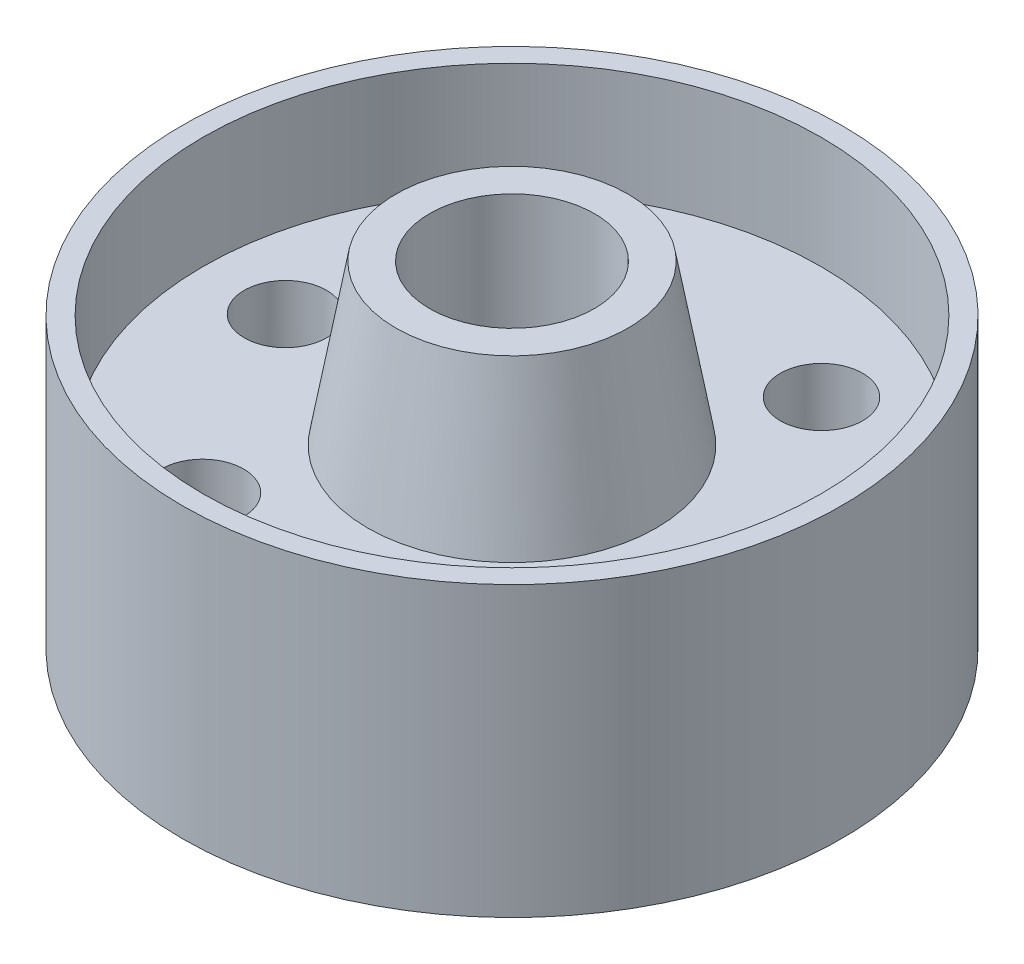
SolidWorks part; units mm, degrees
material "Plain Carbon Steel"
ref_plane "Front" through (0, 0, 0) normal (0, 0, 1) x (1, 0, 0)
ref_plane "Top" through (0, 0, 0) normal (0, 1, 0) x (1, 0, 0)
ref_plane "Right" through (0, 0, 0) normal (1, 0, 0) x (0, 0, -1)
sketch "Sketch1" plane through (0, 0, 0) normal (1, 0, 0) x (0, 0, -1)
  line L0 (0, 0) -> (-38.1, 0) construction
  line L1 (-38.1, 0) -> (-38.1, 22.098)
  line L2 (-38.1, 22.098) -> (-34.925, 22.098)
  line L3 (-34.925, 22.098) -> (-34.925, 4.826)
  line L4 (-34.925, 4.826) -> (-9.525, 4.826)
  line L5 (-9.525, 4.826) -> (-5.1986, 29.3624)
  line L6 (-5.1986, 29.3624) -> (0, 29.3624)
  line L7 (0, 29.3624) -> (0, -29.3624)
  line L8 (12.7, 29.3624) -> (12.7, 0) construction
  line L9 (-34.925, -4.826) -> (-9.525, -4.826)
  line L10 (-9.525, -4.826) -> (-5.1986, -29.3624)
  line L11 (-34.925, -4.826) -> (-34.925, -22.352)
  line L12 (-34.925, -22.352) -> (-38.1, -22.352)
  line L13 (-38.1, -22.352) -> (-38.1, 0)
  line L14 (-5.1986, -29.3624) -> (0, -29.3624)
  dimension "D1" = 25.4
  dimension "D2" = 10
  dimension "D3" = 29.3624
  dimension "D4" = 4.826
  dimension "D5" = 44.45
  dimension "D6" = 101.6
  dimension "D7" = 95.25
  dimension "D8" = 17.272
  dimension "D9" = 44.45
revolve "Revolve2" add sketch "Sketch1" angle 360 about L8
sketch "Sketch5" plane through (0, 4.826, 0) normal (0, 1, 0) x (1, 0, 0)
  line L0 (0, 12.7) -> (-34.925, 12.7) construction
  line L1 (-34.925, 12.7) -> (-17.4625, 42.9459) construction
  line L2 (-17.4625, 42.9459) -> (0, 12.7) construction
  line L3 (0, 12.7) -> (17.4625, 42.9459) construction
  line L4 (17.4625, 42.9459) -> (34.925, 12.7) construction
  line L5 (34.925, 12.7) -> (0, 12.7) construction
  line L6 (0, 12.7) -> (17.4625, -17.5459) construction
  line L7 (17.4625, -17.5459) -> (-17.4625, -17.5459) construction
  line L8 (-17.4625, -17.5459) -> (0, 12.7) construction
  circle A0 centre (0, 12.7) radius 34.925 construction
  circle A1 centre (-34.925, 12.7) radius 6.35
  circle A2 centre (34.925, 12.7) radius 6.35
  circle A3 centre (-17.4625, 42.9459) radius 6.35
  circle A4 centre (17.4625, 42.9459) radius 6.35
  circle A5 centre (-17.4625, -17.5459) radius 6.35
  circle A6 centre (17.4625, -17.5459) radius 6.35
  dimension "D1" = 60
extrude "Cut-Extrude1" cut sketch "Sketch5" against normal through all
